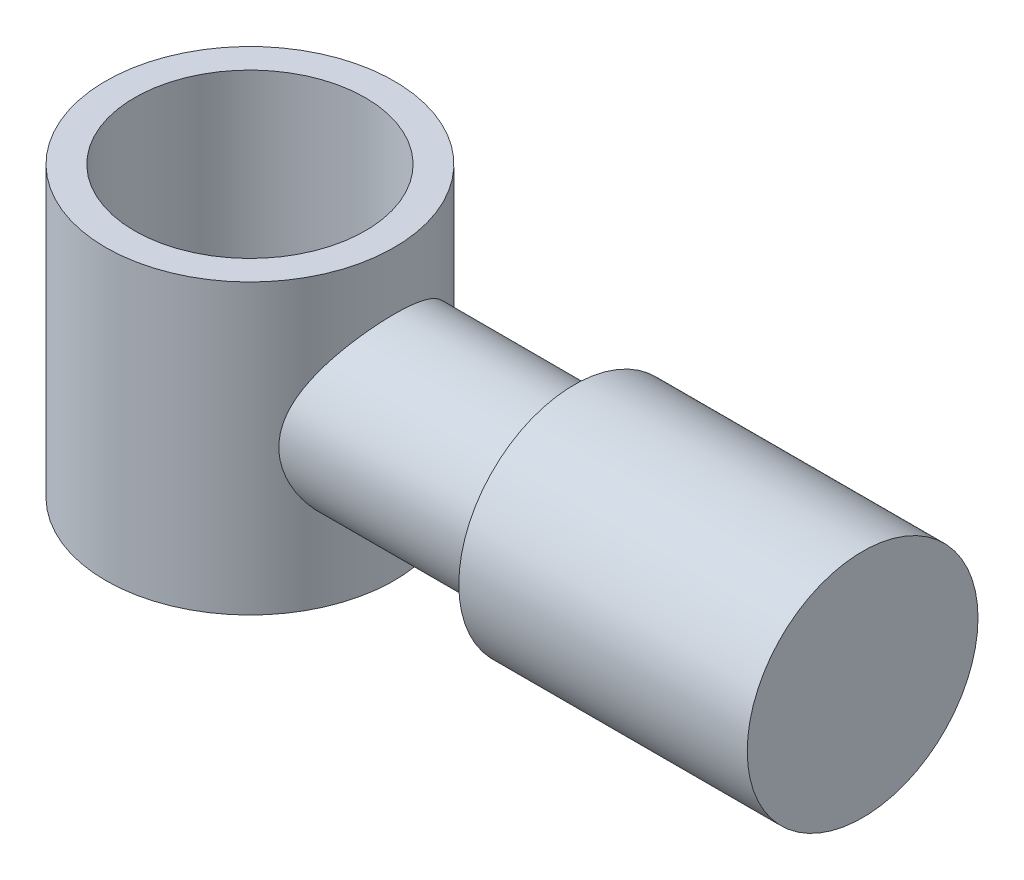
SolidWorks part; units mm, degrees
ref_plane "前视基准面" through (0, 0, 0) normal (0, 0, 1) x (1, 0, 0)
ref_plane "上视基准面" through (0, 0, 0) normal (0, 1, 0) x (1, 0, 0)
ref_plane "右视基准面" through (0, 0, 0) normal (1, 0, 0) x (0, 0, -1)
sketch "草图1" plane through (0, 0, 0) normal (0, 1, 0) x (1, 0, 0)
  circle A0 centre (0, 0) radius 50
  circle A1 centre (0, 0) radius 40
extrude "凸台-拉伸1" add sketch "草图1" along normal mid plane 100 contours A0 | A1
ref_plane "基准面1" through (162.4, 0, 0) normal (1, 0, 0) x (0, 0, -1)
sketch "草图2" plane through (162.4, 0, 0) normal (1, 0, 0) x (0, 0, -1)
  circle A0 centre (0, 0) radius 40
extrude "凸台-拉伸2" add sketch "草图2" along normal mid plane 100 separate body
sketch "草图4" plane through (112.4, 0, 0) normal (-1, 0, 0) x (0, 0, 1)
  circle A0 centre (0, 0) radius 30
extrude "凸台-拉伸3" add sketch "草图4" along normal up to next separate body contours A0
